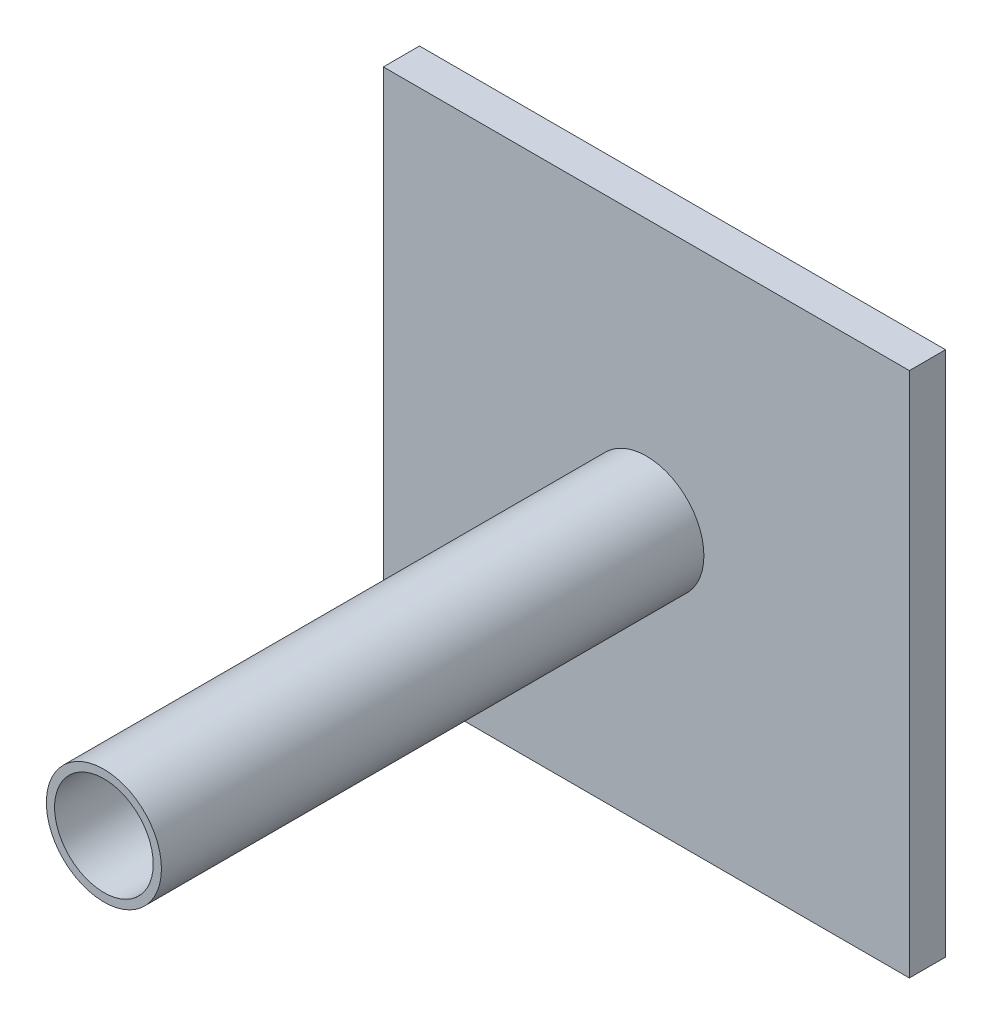
SolidWorks part; units mm, degrees
ref_plane "Plan de face" through (0, 0, 0) normal (0, 0, 1) x (1, 0, 0)
ref_plane "Plan de dessus" through (0, 0, 0) normal (0, 1, 0) x (1, 0, 0)
ref_plane "Plan de droite" through (0, 0, 0) normal (1, 0, 0) x (0, 0, -1)
sketch "Esquisse1" plane through (0, 0, 0) normal (0, 0, 1) x (1, 0, 0)
  line L1 (-17.8486, 18.1673) -> (14.1514, 18.1673)
  line L2 (-17.8486, 18.1673) -> (-17.8486, -13.8327)
  line L3 (-17.8486, -13.8327) -> (14.1514, -13.8327)
  line L4 (14.1514, 18.1673) -> (14.1514, -13.8327)
  dimension "D1" = 32
  dimension "D2" = 32
extrude "Boss.-Extru.1" add sketch "Esquisse1" along normal blind 2.2
sketch "Esquisse2" plane through (0, 0, 2.2) normal (0, 0, 1) x (1, 0, 0)
  line L0 (14.1514, 18.1673) -> (-17.8486, 18.1673) construction
  line L1 (14.1514, -13.8327) -> (14.1514, 18.1673) construction
  circle A0 centre (-1.8486, 2.1673) radius 3.5
  dimension "D1" = 16
  dimension "D3" = 7
  dimension "D2" = 16
extrude "Boss.-Extru.2" add sketch "Esquisse2" along normal blind 33
sketch "Esquisse3" plane through (0, 0, 35.2) normal (0, 0, 1) x (1, 0, 0)
  circle A0 centre (-1.8486, 2.1673) radius 3
extrude "Enlèv. mat.-Extru.1" cut sketch "Esquisse3" against normal through all
